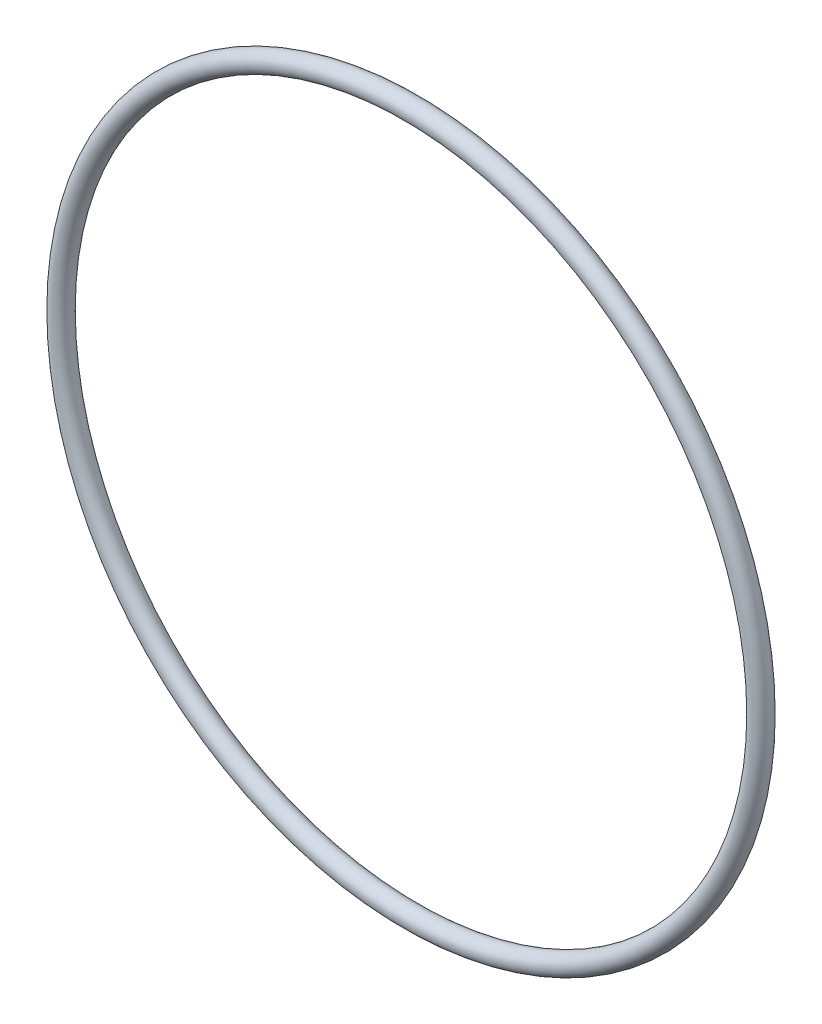
SolidWorks part; units mm, degrees
ref_plane "Front Plane" through (0, 0, 0) normal (0, 0, 1) x (1, 0, 0)
ref_plane "Top Plane" through (0, 0, 0) normal (0, 1, 0) x (1, 0, 0)
ref_plane "Right Plane" through (0, 0, 0) normal (1, 0, 0) x (0, 0, -1)
sketch "Sketch-Path" plane through (0, 0, 0) normal (0, 0, 1) x (1, 0, 0)
  circle A0 centre (0, 0) radius 55.245
  dimension "D1" = 110.49
sweep "Base-Sweep" add path "Sketch-Path" circular profile diameter 3.175 parameters "D3"=3.175
